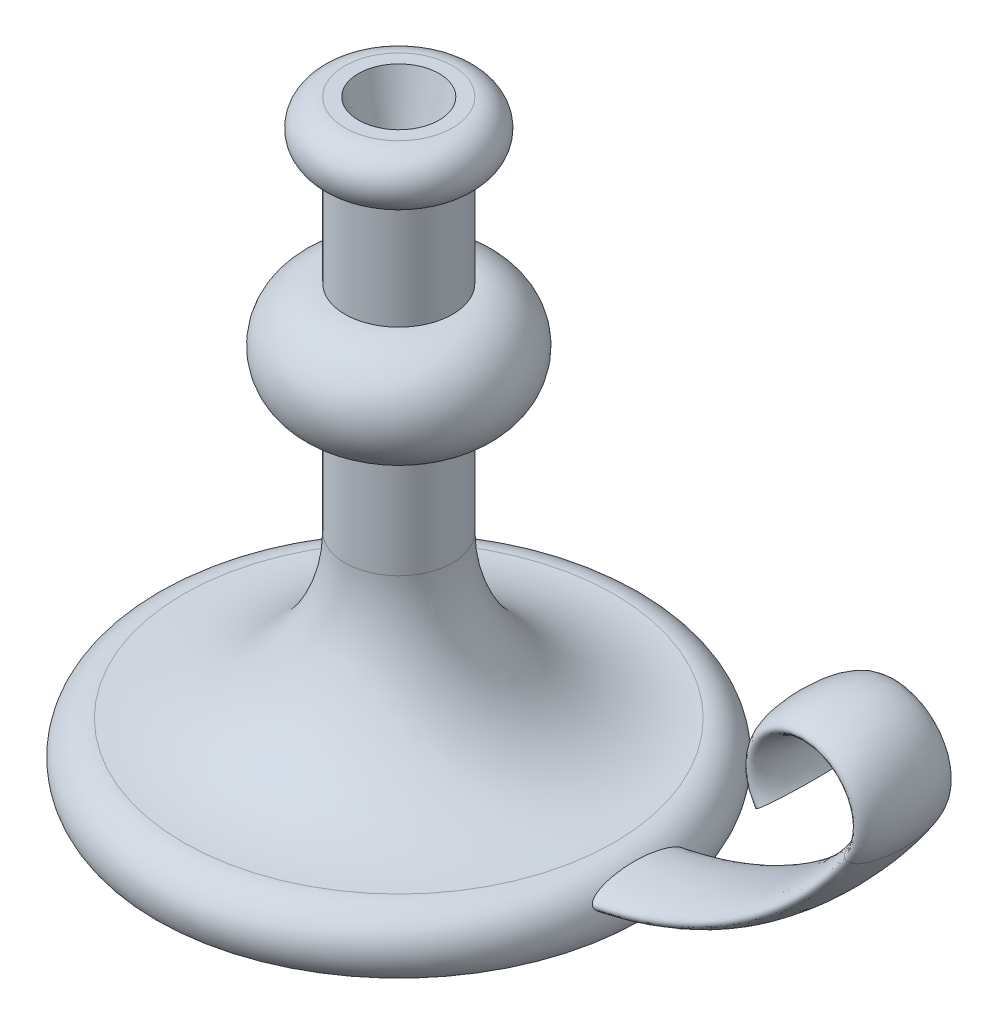
SolidWorks part; units mm, degrees
ref_plane "Front" through (0, 0, 0) normal (0, 0, 1) x (1, 0, 0)
ref_plane "Top" through (0, 0, 0) normal (0, 1, 0) x (1, 0, 0)
ref_plane "Right" through (0, 0, 0) normal (1, 0, 0) x (0, 0, -1)
sketch "草图1" plane through (0, 0, 0) normal (0, 0, 1) x (1, 0, 0)
  line L0 (0, 0) -> (90, 0)
  line L1 (90, 0) -> (0, 0)
  line L2 (0, 220) -> (0, 0)
  line L3 (0, 220) -> (20, 220)
  line L4 (20, 220) -> (0, 220)
  line L5 (20, 200) -> (20, 160)
  line L6 (20, 120) -> (20, 80)
  arc A0 (20, 220) -> (20, 200) centre (20, 210) cw
  arc A1 (20, 160) -> (20, 120) centre (20, 140) cw
  arc A2 (20, 80) -> (80, 20) centre (80, 80) ccw
  arc A3 (80, 20) -> (90, 0) centre (80, 7.5) cw
  point P7 (30, 210)
  dimension "D5" = 20
  dimension "D7" = 60
  dimension "D9" = 12.5
  dimension "D1" = 90
  dimension "D2" = 220
  dimension "D3" = 20
  dimension "D4" = 10
  dimension "D6" = 40
  dimension "D8" = 80
revolve "旋转3" add sketch "草图1" angle 360 about L2
sketch "草图2" plane through (0, 0, 0) normal (0, 0, 1) x (1, 0, 0)
  line L0 (0, 10) -> (60, 10)
  line L1 (0, 116) -> (0, 188) construction
  line L2 (0, 33.1812) -> (0, 173.6376) construction
  line L3 (-90, 0) -> (90, 0) construction
  arc A0 (60, 10) -> (183.5921, 75) centre (60, 160) ccw
  arc A1 (183.5921, 75) -> (150.6342, 75) centre (167.1131, 86.3333) ccw
  dimension "D2" = 150
  dimension "D4" = 20
  dimension "D1" = 60
  dimension "D3" = 65
  dimension "D5" = 10
sketch "草图4" plane through (0, 0, 0) normal (1, 0, 0) x (0, 0, -1)
  ellipse E0 centre (0, 10) end of major axis (17.5, 10) minor radius 5
  dimension "D1" = 10
  dimension "D2" = 35
sweep "扫描1" add profiles "草图4" path "草图2"
sketch "草图6" plane through (0, 220, 0) normal (0, 1, 0) x (1, 0, 0)
  circle A0 centre (0, 0) radius 15
  dimension "D1" = 30
extrude "切除-拉伸1" cut sketch "草图6" against normal blind 25 draft 15
